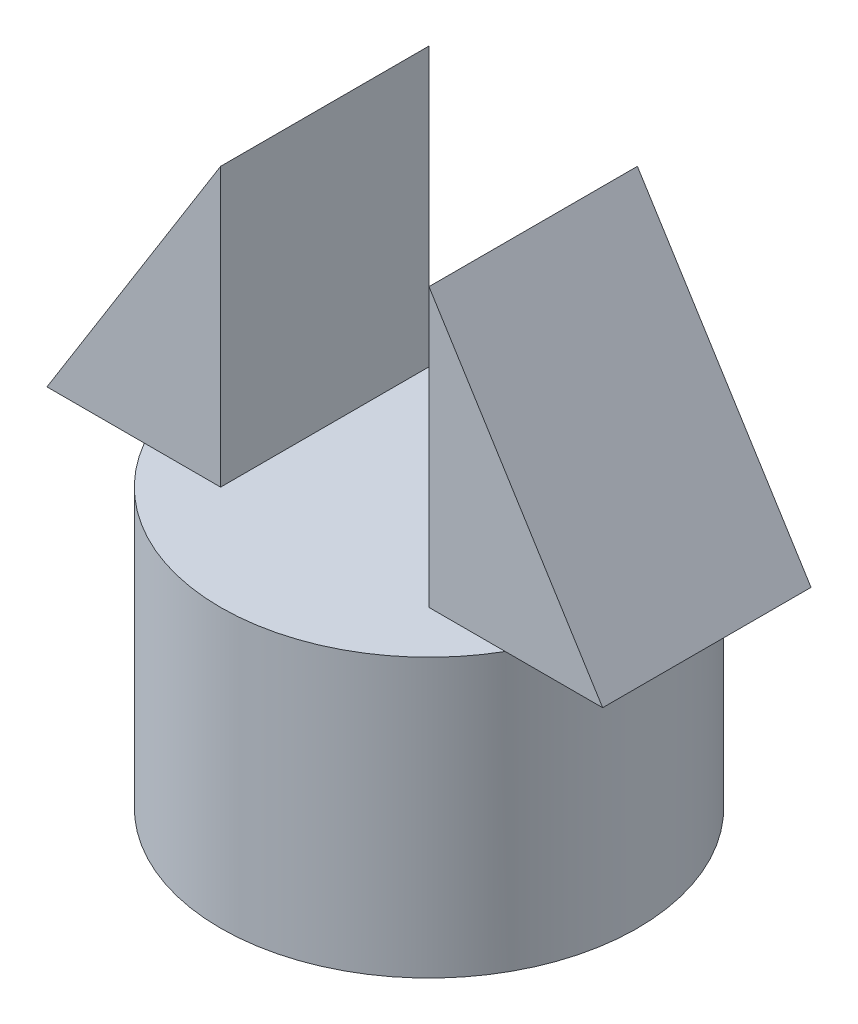
SolidWorks part; units mm, degrees
ref_plane "前视基准面" through (0, 0, 0) normal (0, 0, 1) x (1, 0, 0)
ref_plane "上视基准面" through (0, 0, 0) normal (0, 1, 0) x (1, 0, 0)
ref_plane "右视基准面" through (0, 0, 0) normal (1, 0, 0) x (0, 0, -1)
other "Configuration Table"
sketch "草图1" plane through (0, 0, 0) normal (0, 1, 0) x (1, 0, 0)
  circle A0 centre (0, 0) radius 30
  dimension "D1" = 60
extrude "凸台-拉伸1" add sketch "草图1" along normal blind 40
sketch "草图2" plane through (0, 0, 0) normal (0, 0, 1) x (1, 0, 0)
  line L0 (-15, 40) -> (-15, 80)
  line L1 (30, 40) -> (-30, 40) construction
  line L2 (-15, 40) -> (-40, 40)
  line L3 (-40, 40) -> (-15, 80)
  line L4 (-30, 40) -> (-30, 0) construction
  line L5 (0, 0) -> (0, 84.8515) construction
  line L6 (15, 40) -> (40, 40)
  line L7 (15, 40) -> (15, 80)
  line L8 (40, 40) -> (15, 80)
  point P4 (-30, 40)
  dimension "D1" = 40
  dimension "D2" = 25
  dimension "D3" = 15
extrude "凸台-拉伸2" add sketch "草图2" along normal mid plane 30
